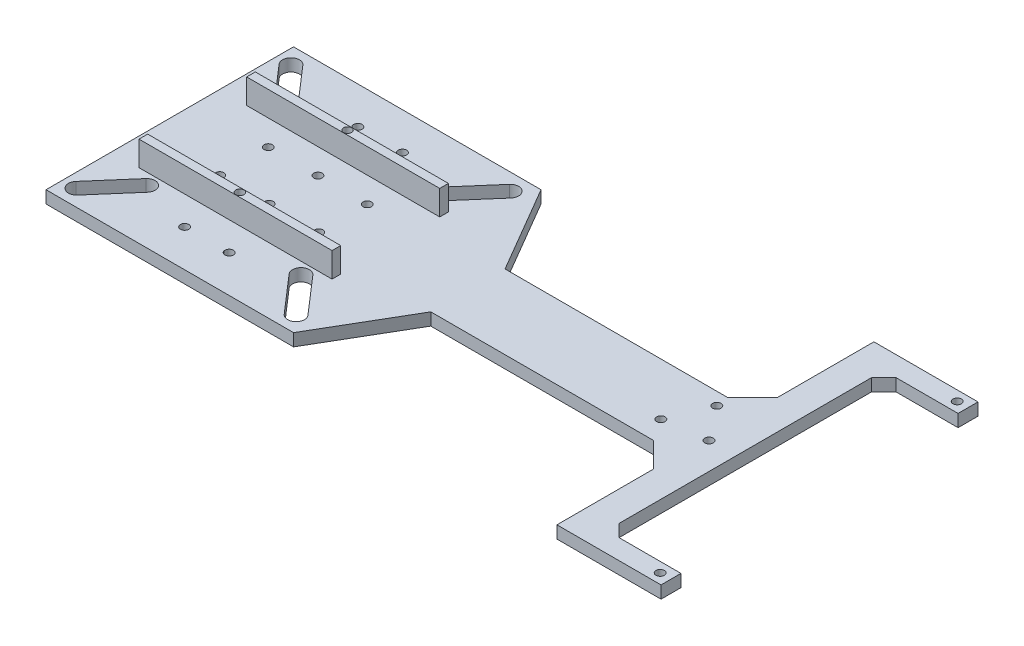
SolidWorks part; units mm, degrees
ref_plane "Front Plane" through (0, 0, 0) normal (0, 0, 1) x (1, 0, 0)
ref_plane "Top Plane" through (0, 0, 0) normal (0, 1, 0) x (1, 0, 0)
ref_plane "Right Plane" through (0, 0, 0) normal (1, 0, 0) x (0, 0, -1)
sketch "Sketch1" plane through (0, 0, 0) normal (0, 1, 0) x (1, 0, 0)
  line L0 (137.5, 44.5853) -> (137.5, 5.5556)
  line L2 (-82.9545, 119.5853) -> (-82.9545, 19.5853)
  line L3 (-82.9545, 19.5853) -> (17.0455, 19.5853)
  line L7 (37.5, 54.5853) -> (127.5, 54.5853)
  line L10 (137.5, -19.0341) -> (137.5, -19.5455)
  line L11 (137.5, 5.5556) -> (149.5541, 5.5556)
  line L17 (154.5541, 13.6149) -> (179.5541, 13.6149)
  line L19 (149.5541, 5.5556) -> (179.5541, 5.5556)
  line L20 (179.5541, 13.6149) -> (179.5541, 5.5556)
  line L25 (37.5, 84.5853) -> (17.0455, 119.5853)
  line L26 (179.5541, 125.5556) -> (179.5541, 133.6149)
  line L27 (-82.9545, 69.5853) -> (149.5541, 69.5853) construction
  line L28 (37.5, 54.5853) -> (17.0455, 19.5853)
  line L29 (149.5541, 120.5556) -> (149.5541, 18.6149)
  line L30 (149.5541, 133.6149) -> (179.5541, 133.6149)
  line L31 (154.5541, 125.5556) -> (179.5541, 125.5556)
  line L32 (137.5, 133.6149) -> (149.5541, 133.6149)
  line L33 (37.5, 84.5853) -> (127.5, 84.5853)
  line L34 (-82.9545, 119.5853) -> (17.0455, 119.5853)
  line L35 (137.5, 94.5853) -> (137.5, 133.6149)
  line L36 (127.5, 54.5853) -> (137.5, 44.5853)
  line L37 (127.5, 84.5853) -> (137.5, 94.5853)
  line L38 (-77.2356, 26.3314) -> (-64.1214, 41.4317) construction
  line L39 (-79.8027, 28.5608) -> (-66.6885, 43.6611)
  line L40 (-74.6686, 24.102) -> (-61.5544, 39.2023)
  line L41 (-32.9545, 119.5853) -> (-32.9545, 19.5853) construction
  line L42 (-77.2356, 112.8391) -> (-64.1214, 97.7389) construction
  line L45 (179.5541, 9.5853) -> (137.5, 9.5853) construction
  line L46 (149.5541, 18.6149) -> (154.5541, 13.6149)
  line L47 (149.5541, 120.5556) -> (154.5541, 125.5556)
  line L48 (-79.8027, 110.6097) -> (-66.6885, 95.5094)
  line L49 (-74.6686, 115.0685) -> (-61.5544, 99.9683)
  line L50 (11.3265, 112.8391) -> (-1.7876, 97.7389) construction
  line L51 (13.8936, 110.6097) -> (0.7794, 95.5094)
  line L52 (8.7595, 115.0685) -> (-4.3547, 99.9683)
  line L53 (11.3265, 26.3314) -> (-1.7876, 41.4317) construction
  line L54 (13.8936, 28.5608) -> (0.7794, 43.6611)
  line L55 (8.7595, 24.102) -> (-4.3547, 39.2023)
  line L57 (-71.8851, 49.5853) -> (6.1149, 49.5853)
  line L58 (-71.8851, 49.5853) -> (-71.8851, 46.0853)
  line L59 (-71.8851, 46.0853) -> (6.1149, 46.0853)
  line L60 (6.1149, 49.5853) -> (6.1149, 46.0853)
  line L61 (-71.8851, 93.0853) -> (6.1149, 93.0853)
  line L62 (6.1149, 89.5853) -> (6.1149, 93.0853)
  line L63 (-71.8851, 89.5853) -> (6.1149, 89.5853)
  line L64 (-71.8851, 89.5853) -> (-71.8851, 93.0853)
  circle A0 centre (129.4825, 69.5853) radius 15
  circle A1 centre (138.7265, 65.771) radius 1.7
  circle A2 centre (121.5573, 63.4869) radius 1.7
  circle A3 centre (128.1638, 79.4979) radius 1.7
  arc A4 (-79.8027, 28.5608) -> (-74.6686, 24.102) centre (-77.2356, 26.3314) ccw
  arc A5 (-61.5544, 39.2023) -> (-66.6885, 43.6611) centre (-64.1214, 41.4317) ccw
  circle A8 centre (175.1739, 9.5853) radius 1.7
  circle A9 centre (175.1739, 129.5853) radius 1.7
  arc A10 (-79.8027, 110.6097) -> (-74.6686, 115.0685) centre (-77.2356, 112.8391) cw
  arc A11 (-61.5544, 99.9683) -> (-66.6885, 95.5094) centre (-64.1214, 97.7389) cw
  arc A12 (13.8936, 110.6097) -> (8.7595, 115.0685) centre (11.3265, 112.8391) ccw
  arc A13 (-4.3547, 99.9683) -> (0.7794, 95.5094) centre (-1.7876, 97.7389) ccw
  arc A14 (13.8936, 28.5608) -> (8.7595, 24.102) centre (11.3265, 26.3314) cw
  arc A15 (-4.3547, 39.2023) -> (0.7794, 43.6611) centre (-1.7876, 41.4317) cw
  point P3 (149.5541, 125.5556)
  point P5 (137.5, 54.5853)
  point P15 (149.5541, 13.6149)
  point P19 (137.5, 84.5853)
  point P27 (-70.6785, 33.8815)
  point P41 (-32.9545, 69.5853)
  point P46 (-70.6785, 105.289)
  point P63 (4.7694, 105.289)
  point P70 (4.7694, 33.8815)
  point P83 (0, 0)
  point P84 (0, 0)
  dimension "D8" = 30
  dimension "D9" = 10
  dimension "D10" = 3.4
  dimension "D12" = 3.4
  dimension "D4" = 3.4
  dimension "D1" = 100
  dimension "D2" = 100
  dimension "D3" = 100
  dimension "D5" = 30
  dimension "D6" = 30
  dimension "D7" = 8.0593
  dimension "D13" = 120
  dimension "D16" = 20
  dimension "D17" = 40.973
  dimension "D20" = 42
  dimension "D21" = 3.5
  dimension "D22" = 78
  dimension "D23" = 20
  dimension "D11" = 3
extrude "Boss-Extrude3" add sketch "Sketch1" along normal blind 5 contours L29 L46 L17 L20 L19 L11 L0 L36 L7 L28 L3 L2 L34 L25 L33 L37 L35 L32 L30 L26 L31 L47 | L54 A15 L55 A14 | L40 A5 L39 A4 | L51 A13 L52 A12 | L48 A11 L49 A10 | A1 | A2 | A3 | A9 | A8
sketch "Sketch5" plane through (0, 5, 0) normal (0, 1, 0) x (1, 0, 0)
  line L1 (-71.8851, 49.5853) -> (6.1149, 49.5853)
  line L2 (-71.8851, 49.5853) -> (-71.8851, 46.0853)
  line L3 (-71.8851, 46.0853) -> (6.1149, 46.0853)
  line L4 (6.1149, 49.5853) -> (6.1149, 46.0853)
  line L5 (-71.8851, 93.0853) -> (6.1149, 93.0853)
  line L6 (-71.8851, 93.0853) -> (-71.8851, 89.5853)
  line L7 (-71.8851, 89.5853) -> (6.1149, 89.5853)
  line L8 (6.1149, 93.0853) -> (6.1149, 89.5853)
extrude "Boss-Extrude4" add sketch "Sketch5" along normal blind 10
sketch "Sketch6" plane through (0, 5, 0) normal (0, 1, 0) x (1, 0, 0)
  line L0 (-32.9545, 119.5853) -> (-32.9545, 19.5853) construction
  line L2 (-82.9545, 69.5853) -> (149.5541, 69.5853) construction
  circle A0 centre (-32.9545, 47.8249) radius 1.65
  circle A1 centre (-32.9545, 59.7011) radius 1.7
  circle A2 centre (-12.9545, 59.7918) radius 1.7
  circle A3 centre (-52.9545, 59.7918) radius 1.7
  circle A4 centre (-32.9545, 91.3457) radius 1.65
  circle A5 centre (-12.9545, 79.3787) radius 1.7
  circle A6 centre (-32.9545, 79.4694) radius 1.7
  circle A7 centre (-52.9545, 79.3787) radius 1.7
  point P22 (0, 0)
  point P23 (0, 0)
  dimension "D1" = 3.3
  dimension "D2" = 3.4
  dimension "D3" = 3.4
  dimension "D4" = 3.4
  dimension "D5" = 20
  dimension "D6" = 20
extrude "Cut-Extrude5" cut sketch "Sketch6" against normal through all
sketch "Sketch8" plane through (0, 15, 0) normal (0, 1, 0) x (1, 0, 0)
  line L0 (-71.8851, 47.8353) -> (6.1149, 47.8353) construction
  line L1 (-71.8851, 49.5853) -> (-71.8851, 46.0853) construction
  line L2 (6.1149, 49.5853) -> (6.1149, 46.0853) construction
  line L3 (-82.9545, 69.5853) -> (149.5541, 69.5853) construction
  line L4 (-82.9545, 119.5853) -> (-82.9545, 19.5853) construction
  circle A0 centre (-32.8851, 47.8353) radius 1.65
  circle A1 centre (-32.8851, 91.3353) radius 1.65
  dimension "D1" = 3.3
extrude "Cut-Extrude6" cut sketch "Sketch8" against normal up to surface (10 mm away) up to face at (-52.9545, 5, -81.0787)
sketch "Sketch9" plane through (0, 5, 0) normal (0, 1, 0) x (1, 0, 0)
  line L0 (-32.9545, 119.5853) -> (-32.9545, 19.5853) construction
  line L1 (-82.9545, 19.5853) -> (17.0455, 19.5853) construction
  line L2 (-82.9545, 69.5853) -> (17.4876, 69.5853) construction
  line L3 (-32.9545, 116.4635) -> (-32.9545, 19.5853) construction
  line L4 (-82.9545, 69.5853) -> (149.5541, 69.5853) construction
  circle A0 centre (-23.9545, 34.5853) radius 1.7
  circle A1 centre (-41.9545, 34.5853) radius 1.7
  circle A2 centre (-41.9545, 104.5853) radius 1.7
  circle A3 centre (-23.9545, 104.5853) radius 1.7
  dimension "D1" = 3.4
  dimension "D2" = 9
  dimension "D3" = 15
extrude "Cut-Extrude8" cut sketch "Sketch9" against normal through all contours A1 | A0 | A3 | A2
